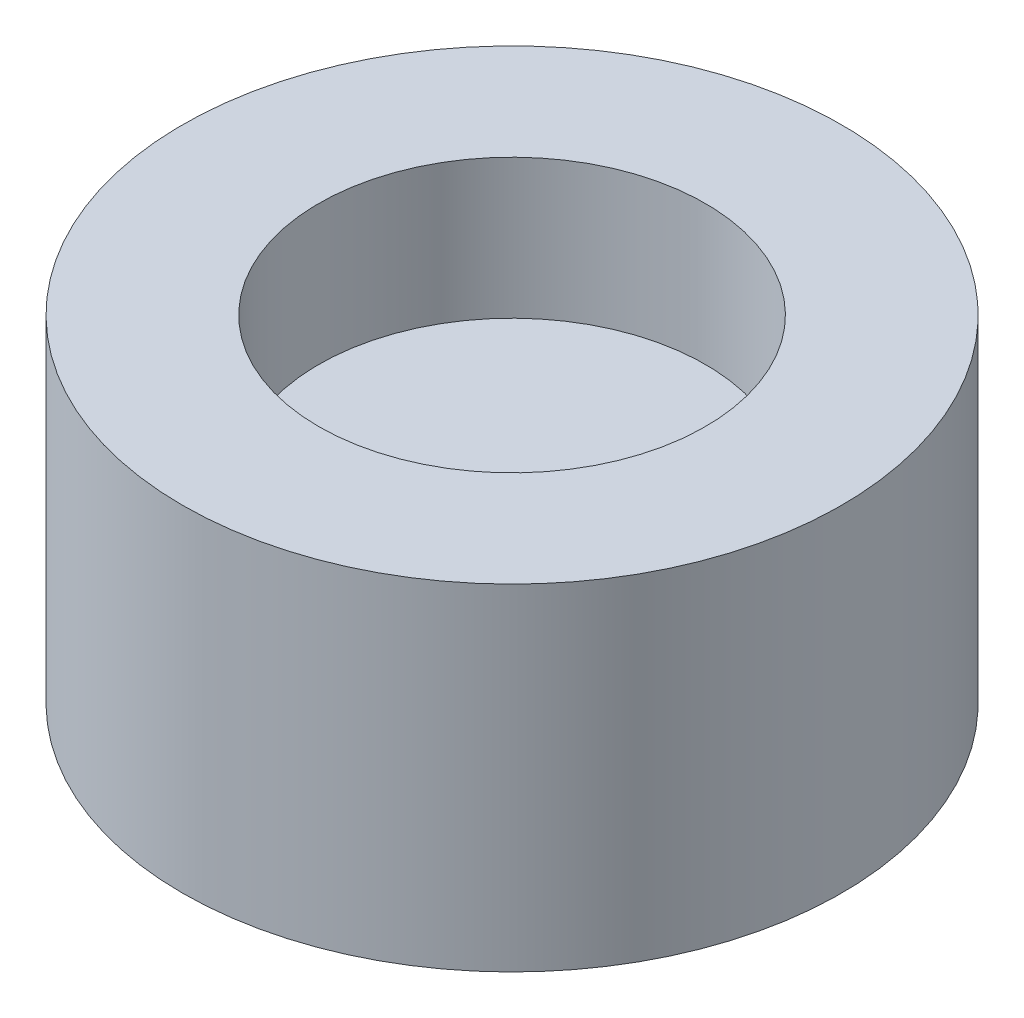
SolidWorks part; units mm, degrees
ref_plane "Alzado" through (0, 0, 0) normal (0, 0, 1) x (1, 0, 0)
ref_plane "Planta" through (0, 0, 0) normal (0, 1, 0) x (1, 0, 0)
ref_plane "Vista lateral" through (0, 0, 0) normal (1, 0, 0) x (0, 0, -1)
sketch "Croquis1" plane through (0, 0, 0) normal (0, 1, 0) x (1, 0, 0)
  circle A0 centre (0, 0) radius 1.65
  circle A1 centre (0, 0) radius 2.95
  dimension "D1" = 3.3
  dimension "D2" = 5.9
extrude "Saliente-Extruir1" add sketch "Croquis1" along normal blind 1.5
sketch "Croquis2" plane through (0, 1.5, 0) normal (0, 1, 0) x (1, 0, 0)
  circle A0 centre (0, 0) radius 5.2
  dimension "D1" = 10.4
extrude "Saliente-Extruir2" add sketch "Croquis2" along normal blind 5.3
sketch "Croquis3" plane through (0, 6.8, 0) normal (0, 1, 0) x (1, 0, 0)
  circle A0 centre (0, 0) radius 3.05
  dimension "D1" = 6.1
extrude "Cortar-Extruir1" cut sketch "Croquis3" against normal blind 2.3
sketch "Croquis4" plane through (0, 0, 0) normal (0, -1, 0) x (1, 0, 0)
  circle A0 centre (0, 0) radius 1.65 construction
  circle A1 centre (0, 0) radius 1.65
extrude "Cortar-Extruir2" cut sketch "Croquis4" against normal blind 4.6
sketch "Croquis5" plane through (0, 4.5, 0) normal (0, 1, 0) x (1, 0, 0)
  circle A0 centre (0, 0) radius 3.05
extrude "Saliente-Extruir3" add sketch "Croquis5" along normal blind 0.1
